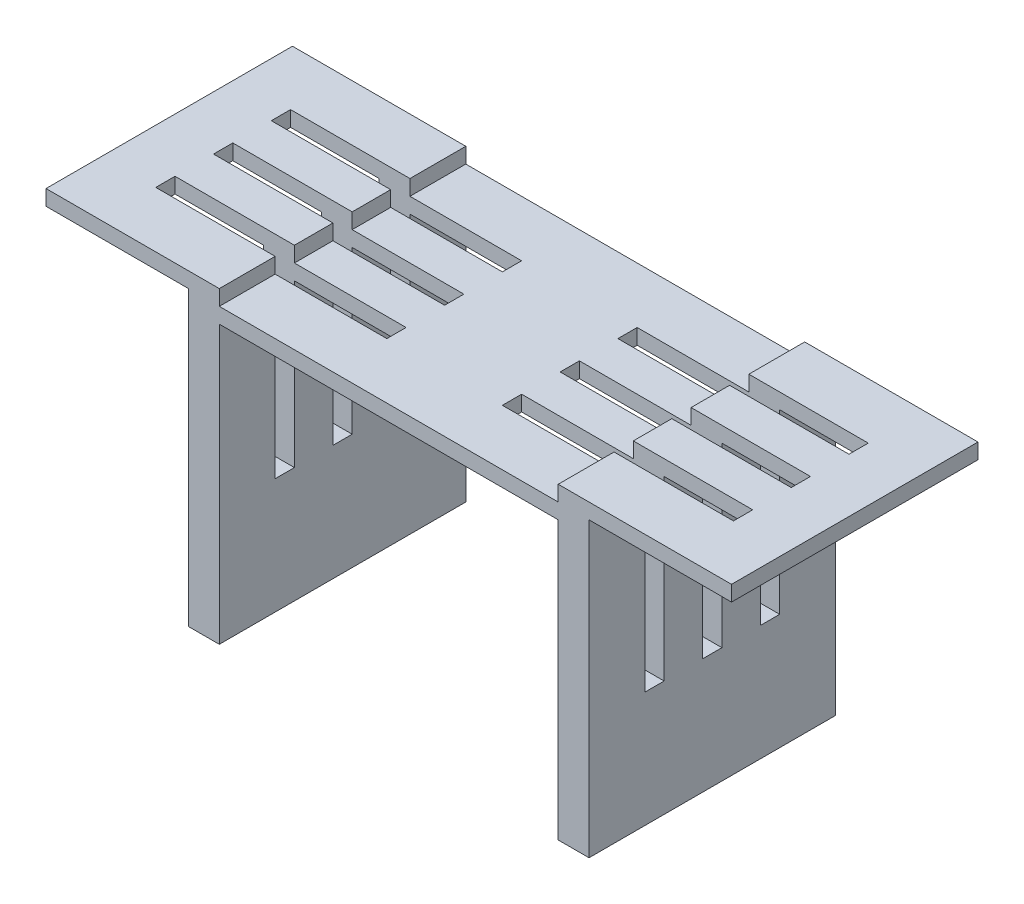
SolidWorks part; units mm, degrees
ref_plane "Front Plane" through (0, 0, 0) normal (0, 0, 1) x (1, 0, 0)
ref_plane "Top Plane" through (0, 0, 0) normal (0, 1, 0) x (1, 0, 0)
ref_plane "Right Plane" through (0, 0, 0) normal (1, 0, 0) x (0, 0, -1)
sketch "Sketch1" plane through (0, 0, 0) normal (0, 0, 1) x (1, 0, 0)
  line L0 (-4.699, 10.16) -> (-4.699, 9.652)
  line L1 (-4.699, 9.652) -> (0, 9.652)
  line L2 (0, 9.652) -> (0, 0)
  line L3 (0, 0) -> (1.016, 0)
  line L4 (1.016, 0) -> (1.016, 9.144)
  line L5 (1.016, 9.144) -> (12.192, 9.144)
  line L6 (12.192, 9.144) -> (12.192, 0)
  line L7 (12.192, 0) -> (13.208, 0)
  line L8 (13.208, 0) -> (13.208, 9.652)
  line L9 (13.208, 9.652) -> (17.907, 9.652)
  line L10 (17.907, 9.652) -> (17.907, 10.16)
  line L11 (17.907, 10.16) -> (12.192, 10.16)
  line L12 (12.192, 10.16) -> (12.192, 9.652)
  line L13 (12.192, 9.652) -> (1.016, 9.652)
  line L14 (1.016, 9.652) -> (1.016, 10.16)
  line L15 (1.016, 10.16) -> (-4.699, 10.16)
  line L16 (12.192, 10.16) -> (1.016, 10.16) construction
  line L17 (6.604, 9.144) -> (6.604, 0) construction
  line L18 (6.604, 0) -> (1.016, 0) construction
  line L19 (6.604, 0) -> (12.192, 0) construction
  line L20 (6.604, 9.144) -> (6.604, 9.652) construction
  line L21 (6.604, 10.16) -> (6.604, 9.652) construction
  point P21 (0, 0)
  point P22 (0, 0)
  dimension "D1" = 1.016
  dimension "D2" = 1.016
  dimension "D3" = 13.208
  dimension "D4" = 0.508
  dimension "D5" = 0.508
  dimension "D6" = 0.508
  dimension "D7" = 22.606
  dimension "D8" = 10.16
extrude "Boss-Extrude1" add sketch "Sketch1" along normal blind 8.128
sketch "Sketch2" plane through (0, 10.16, 0) normal (0, 1, 0) x (1, 0, 0)
  line L0 (6.604, -8.128) -> (6.604, 0) construction
  line L1 (-2.921, -1.8415) -> (4.699, -1.8415)
  line L2 (-2.921, -1.8415) -> (-2.921, -2.4765)
  line L3 (-2.921, -2.4765) -> (4.699, -2.4765)
  line L4 (4.699, -1.8415) -> (4.699, -2.4765)
  line L5 (-2.921, -3.7465) -> (4.699, -3.7465)
  line L6 (-2.921, -3.7465) -> (-2.921, -4.3815)
  line L7 (-2.921, -4.3815) -> (4.699, -4.3815)
  line L8 (4.699, -3.7465) -> (4.699, -4.3815)
  line L9 (-2.921, -5.6515) -> (4.699, -5.6515)
  line L10 (-2.921, -5.6515) -> (-2.921, -6.2865)
  line L11 (-2.921, -6.2865) -> (4.699, -6.2865)
  line L12 (4.699, -5.6515) -> (4.699, -6.2865)
  line L13 (8.509, -1.8415) -> (16.129, -1.8415)
  line L14 (8.509, -1.8415) -> (8.509, -2.4765)
  line L15 (8.509, -2.4765) -> (16.129, -2.4765)
  line L16 (16.129, -1.8415) -> (16.129, -2.4765)
  line L17 (8.509, -3.7465) -> (16.129, -3.7465)
  line L18 (8.509, -3.7465) -> (8.509, -4.3815)
  line L19 (8.509, -4.3815) -> (16.129, -4.3815)
  line L20 (16.129, -3.7465) -> (16.129, -4.3815)
  line L21 (8.509, -5.6515) -> (16.129, -5.6515)
  line L22 (8.509, -5.6515) -> (8.509, -6.2865)
  line L23 (8.509, -6.2865) -> (16.129, -6.2865)
  line L24 (16.129, -5.6515) -> (16.129, -6.2865)
  line L25 (12.192, -8.128) -> (1.016, -8.128) construction
  line L26 (12.192, 0) -> (1.016, 0) construction
  line L27 (4.699, -4.064) -> (6.604, -4.064) construction
  dimension "D1" = 0.635
  dimension "D2" = 7.62
  dimension "D3" = 3.81
  dimension "D4" = 1.27
  dimension "D5" = 1.27
extrude "Cut-Extrude1" cut sketch "Sketch2" against normal offset from surface (6.35 mm away) 3.81 up to face at (0.508, 0, 4.064)
